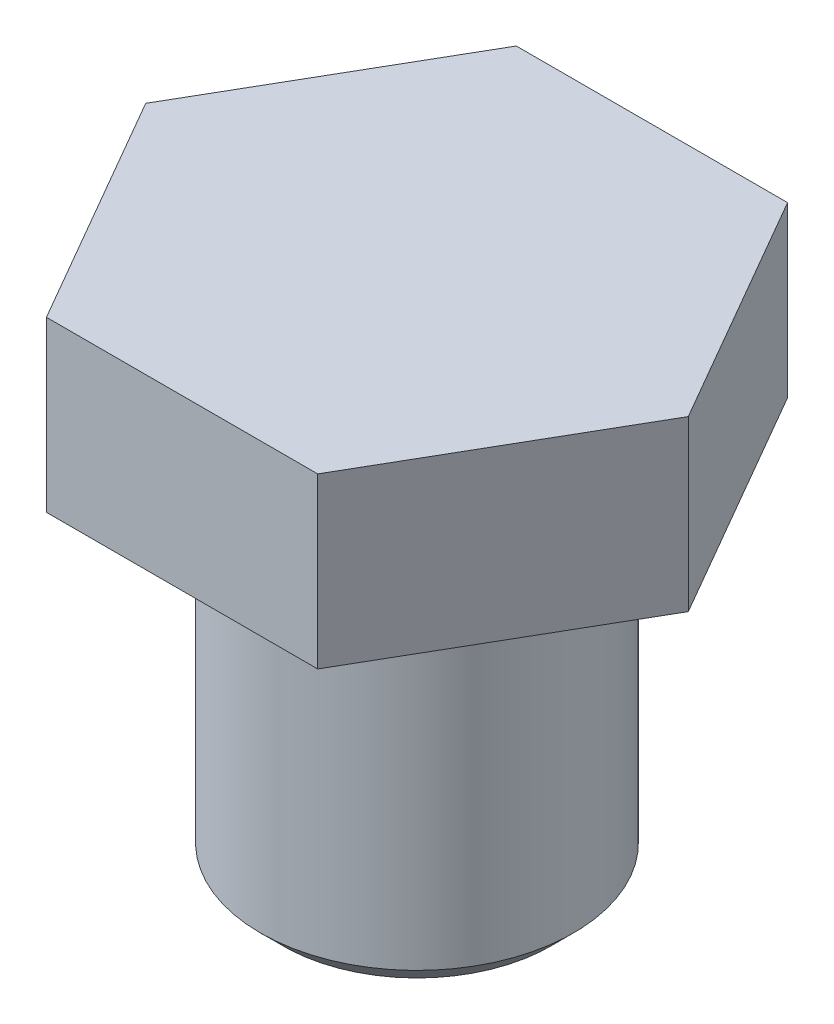
SolidWorks part; units mm, degrees
material "Ст 3 ГОСТ 380-88"
ref_plane "Front Plane" through (0, 0, 0) normal (0, 0, 1) x (1, 0, 0)
ref_plane "Top Plane" through (0, 0, 0) normal (0, 1, 0) x (1, 0, 0)
ref_plane "Right Plane" through (0, 0, 0) normal (1, 0, 0) x (0, 0, -1)
sketch "Sketch1" plane through (0, 0, 0) normal (0, 1, 0) x (1, 0, 0)
  line L0 (-20.1733, 0) -> (20.4178, 0) construction
  line L1 (-12.1244, 0) -> (-6.0622, -10.5)
  line L2 (-6.0622, -10.5) -> (6.0622, -10.5)
  line L3 (6.0622, -10.5) -> (12.1244, 0)
  line L4 (12.1244, 0) -> (6.0622, 10.5)
  line L5 (6.0622, 10.5) -> (-6.0622, 10.5)
  line L6 (-6.0622, 10.5) -> (-12.1244, 0)
  circle A0 centre (0, 0) radius 10.5 construction
  dimension "D1" = 21
  dimension "D2" = 24.2487
extrude "Boss-Extrude1" add sketch "Sketch1" along normal blind 7.55
sketch "Sketch2" plane through (0, 0, 0) normal (0, -1, 0) x (1, 0, 0)
  circle A0 centre (0, 0) radius 7
  dimension "D1" = 14
extrude "Boss-Extrude2" add sketch "Sketch2" along normal blind 16 contours A0
chamfer "Chamfer1" distance 1 angle 45 1 edges at (0, -16, -7)
